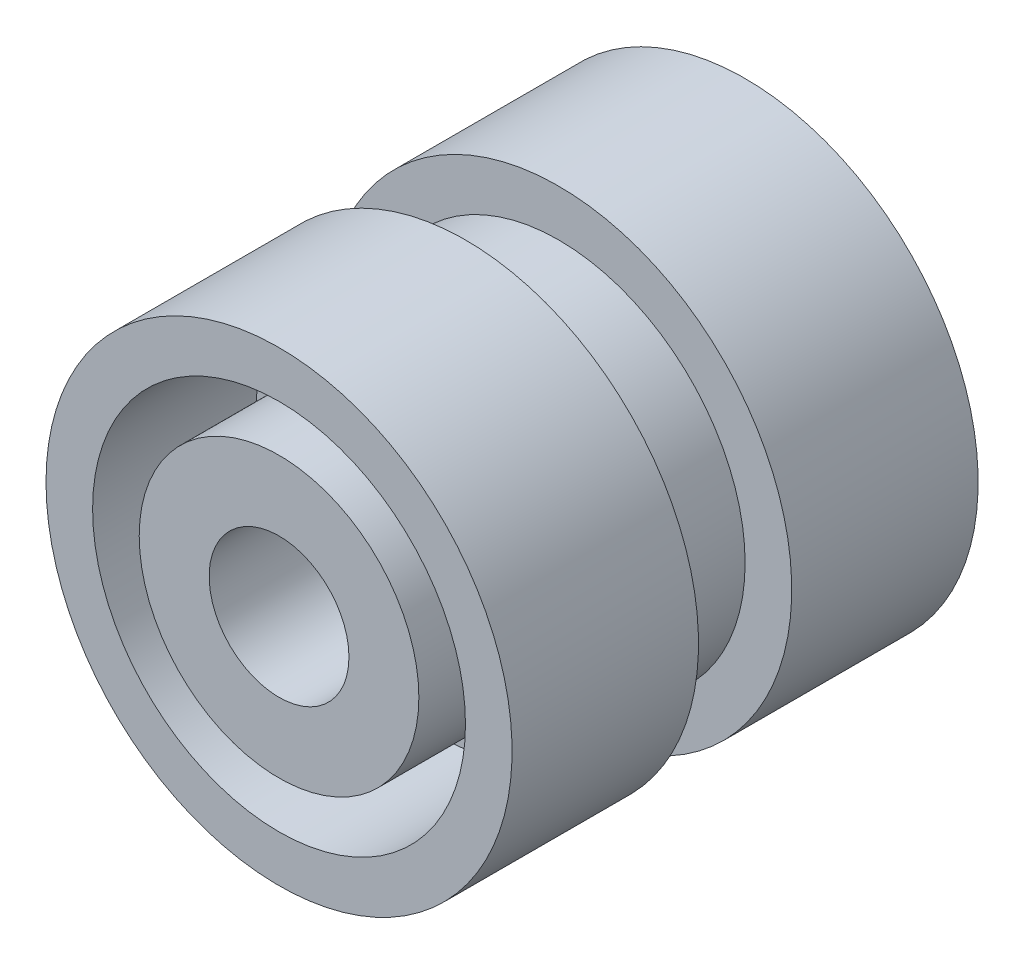
SolidWorks part; units mm, degrees
ref_plane "Front Plane" through (0, 0, 0) normal (0, 0, 1) x (1, 0, 0)
ref_plane "Top Plane" through (0, 0, 0) normal (0, 1, 0) x (1, 0, 0)
ref_plane "Right Plane" through (0, 0, 0) normal (1, 0, 0) x (0, 0, -1)
sketch "Sketch2" plane through (0, 0, 0) normal (1, 0, 0) x (0, 0, -1)
  line L0 (0, 0) -> (-10.0693, 0) construction
  line L1 (0, 0) -> (-5, 0)
  line L2 (-5, 0) -> (-5, 3)
  line L3 (-5, 3) -> (-1.5, 3)
  line L4 (-1.5, 3) -> (-1.5, 4)
  line L5 (-1.5, 4) -> (-5, 4)
  line L6 (-5, 4) -> (-5, 5)
  line L7 (-5, 5) -> (-1, 5)
  line L8 (-1, 5) -> (-1, 4)
  line L9 (-1, 4) -> (1, 4)
  line L10 (0, 4) -> (0, 0) construction
  line L11 (1, 5) -> (1, 4)
  line L12 (5, 5) -> (1, 5)
  line L13 (5, 4) -> (5, 5)
  line L14 (1.5, 4) -> (5, 4)
  line L15 (1.5, 4) -> (1.5, 0)
  line L16 (1.5, 0) -> (0, 0)
  point P17 (-10.0693, 0)
  dimension "D1" = 5
  dimension "D2" = 3
  dimension "D3" = 3.5
  dimension "D4" = 3.5
  dimension "D5" = 1
  dimension "D6" = 1
  dimension "D7" = 1
  dimension "D8" = 1
revolve "Revolve1" add sketch "Sketch2" angle 360 about L0
sketch "Sketch3" plane through (0, 0, -1.5) normal (0, 0, -1) x (-1, 0, 0)
  line L0 (0, 0) -> (0, 4) construction
  line L1 (0.5, 1.9365) -> (0.5, 3.9686)
  line L2 (-0.5, 1.9365) -> (-0.5, 3.9686)
  line L3 (1.9365, -0.5) -> (3.9686, -0.5)
  line L4 (-0.5, 0) -> (-0.5, 4) construction
  line L5 (0.5, 0) -> (0.5, 4) construction
  line L6 (1.9365, 0.5) -> (3.9686, 0.5)
  line L7 (-0.5, -1.9365) -> (-0.5, -3.9686)
  line L8 (0.5, -1.9365) -> (0.5, -3.9686)
  line L9 (-1.9365, 0.5) -> (-3.9686, 0.5)
  line L10 (-1.9365, -0.5) -> (-3.9686, -0.5)
  circle A0 centre (0, 0) radius 4 construction
  arc A1 (-3.9686, 0.5) -> (-3.9686, -0.5) centre (0, 0) ccw
  arc A2 (-1.9365, -0.5) -> (-0.5, -1.9365) centre (0, 0) ccw
  arc A3 (0.5, -1.9365) -> (1.9365, -0.5) centre (0, 0) ccw
  arc A4 (1.9365, 0.5) -> (0.5, 1.9365) centre (0, 0) ccw
  arc A5 (-0.5, 1.9365) -> (-1.9365, 0.5) centre (0, 0) ccw
  arc A6 (0.5, 3.9686) -> (-0.5, 3.9686) centre (0, 0) ccw
  arc A7 (3.9686, -0.5) -> (3.9686, 0.5) centre (0, 0) ccw
  arc A8 (-0.5, -3.9686) -> (0.5, -3.9686) centre (0, 0) ccw
  point P28 (0, 0)
  dimension "D1" = 4
  dimension "D2" = 0.5
  dimension "D3" = 0.5
  dimension "D4" = 4
extrude "Boss-Extrude1" add sketch "Sketch3" along normal blind 2
sketch "Sketch4" plane through (0, 0, 5) normal (0, 0, 1) x (1, 0, 0)
  circle A0 centre (0, 0) radius 1.5
  dimension "D1" = 3
extrude "Cut-Extrude1" cut sketch "Sketch4" against normal blind 8
